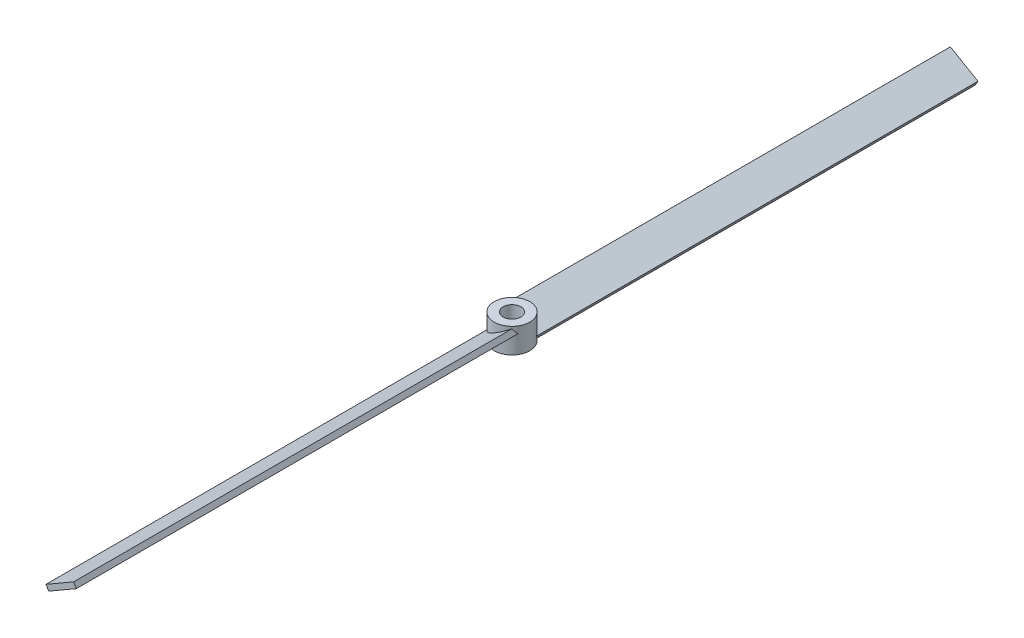
SolidWorks part; units mm, degrees
ref_plane "前视基准面" through (0, 0, 0) normal (0, 0, 1) x (1, 0, 0)
ref_plane "上视基准面" through (0, 0, 0) normal (0, 1, 0) x (1, 0, 0)
ref_plane "右视基准面" through (0, 0, 0) normal (1, 0, 0) x (0, 0, -1)
sketch "草图1" plane through (0, 0, 0) normal (0, 1, 0) x (1, 0, 0)
  circle A2 centre (0, 0) radius 5
  dimension "D1" = 10
extrude "凸台-拉伸1" add sketch "草图1" along normal blind 7
sketch "草图3" plane through (0, 0, 0) normal (0, 0, 1) x (1, 0, 0)
  line L0 (0, 7) -> (0, 0) construction
  line L1 (5, 7) -> (-5, 7) construction
  line L2 (-4.2721, 1.8995) -> (3.5221, 6.3995)
  line L3 (-4.2721, 1.8995) -> (-3.5221, 0.6005)
  line L4 (3.5221, 6.3995) -> (4.2721, 5.1005)
  line L5 (-3.5221, 0.6005) -> (4.2721, 5.1005)
  line L6 (3.8971, 5.75) -> (-3.8971, 1.25) construction
  line L7 (-0.375, 4.1495) -> (0.375, 2.8505) construction
  line L8 (-5, 0) -> (5, 0) construction
  point P6 (0, 3.5)
  point P8 (0, 3.5)
  dimension "D1" = 30
  dimension "D2" = 9
  dimension "D3" = 1.5
extrude "凸台-拉伸2" add sketch "草图3" along normal blind 127
sketch "草图4" plane through (0, 0, 0) normal (0, 0, 1) x (1, 0, 0)
  line L0 (0, 0) -> (0, 7) construction
  line L1 (5, 7) -> (-5, 7) construction
pattern_circular "阵列(圆周)1" count 2 over 360 about axis through (0, 0, 0) along (0, 1, 0) of "凸台-拉伸2"
sketch "草图2" plane through (0, 7, 0) normal (0, 1, 0) x (1, 0, 0)
  circle A0 centre (0, 0) radius 2.5
  dimension "D1" = 5
extrude "切除-拉伸1" cut sketch "草图2" against normal up to next
sketch "草图5" plane through (0, 0, 0) normal (0, 1, 0) x (1, 0, 0)
  circle A0 centre (0, 0) radius 127
  dimension "D1" = 254
